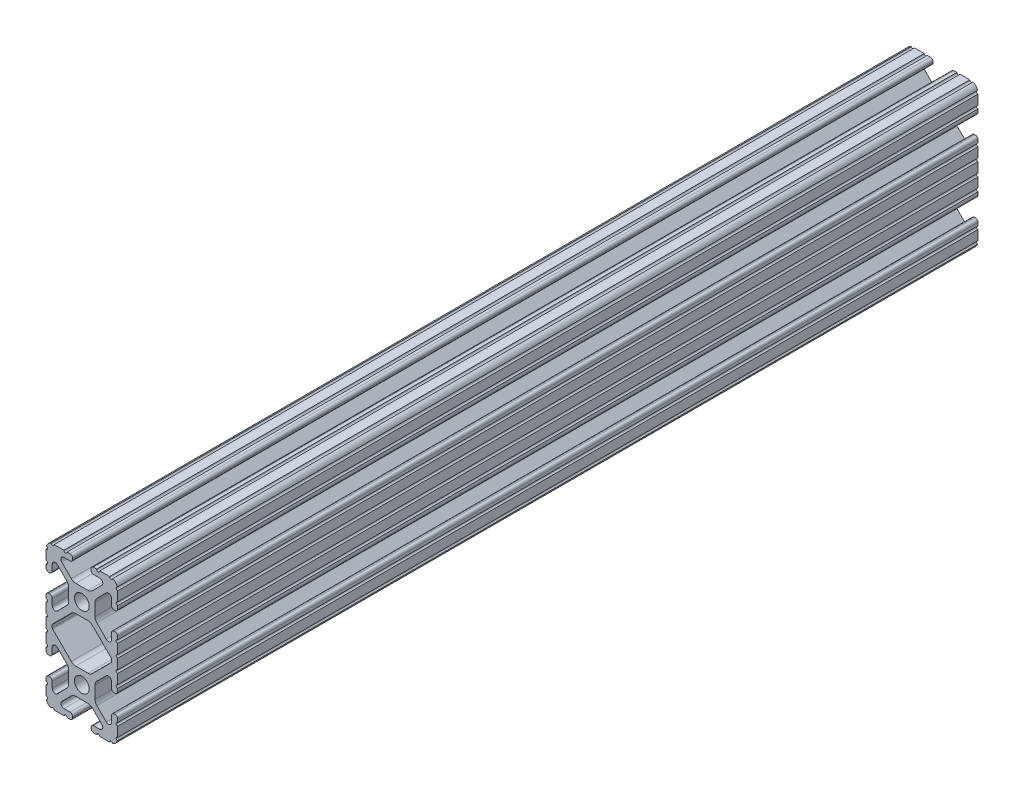
SolidWorks part; units mm, degrees
ref_plane "Front Plane" through (0, 0, 0) normal (0, 0, 1) x (1, 0, 0)
ref_plane "Top Plane" through (0, 0, 0) normal (0, 1, 0) x (1, 0, 0)
ref_plane "Right Plane" through (0, 0, 0) normal (1, 0, 0) x (0, 0, -1)
sketch "Sketch2" plane through (0, 0, 0) normal (0, 0, 1) x (1, 0, 0)
  line L0 (0, 25.4) -> (0, -25.4) construction
  line L1 (-12.7, 0) -> (12.7, 0) construction
  line L2 (3.2512, -25.4) -> (12.7, -25.4)
  line L3 (12.7, -25.4) -> (12.7, -15.9512)
  line L4 (3.2512, -25.4) -> (3.2512, -23.1902)
  line L5 (3.2512, -23.1902) -> (8.9276, -23.1902)
  line L6 (8.9276, -23.1902) -> (3.0856, -17.3482)
  line L7 (0, -12.7) -> (12.7, -25.4) construction
  line L8 (12.7, -15.9512) -> (10.4902, -15.9512)
  line L9 (10.4902, -15.9512) -> (10.4902, -21.6276)
  line L10 (10.4902, -21.6276) -> (4.6482, -15.7856)
  circle A0 centre (0, -12.7) radius 2.6035
  arc A1 (6.3485, -23.1902) -> (7.1039, -21.3665) centre (6.3485, -22.1219) ccw construction
  point P8 (0, -17.3482)
  dimension "Center Hole Diameter" = 5.207
  dimension "Rail Height" = 50.8
  dimension "Rail Width" = 25.4
  dimension "T-Slot Width" = 6.5024
  dimension "Slot Inner Width" = 14.8336
  dimension "Thickness" = 2.2098
  dimension "Slot Depth" = 5.842
  dimension "D1" = 2.2098
  dimension "C to C" = 25.4
sketch "Sketch3" plane through (0, 0, 0) normal (1, 0, 0) x (0, 0, -1)
  line L0 (-152.4, -25.4) -> (152.4, -25.4) construction
  line L1 (-127, 0) -> (127, 0) construction
  dimension "Length" = 304.8
  dimension "D1" = 25.4
sketch "Sketch4" plane through (0, 0, 0) normal (0, 0, 1) x (1, 0, 0)
  line L0 (4.1904, -25.4) -> (10.1173, -25.4)
  line L1 (3.2512, -25.4) -> (12.7, -25.4) construction
  line L2 (3.2512, -25.4) -> (3.2512, -23.1902) construction
  line L3 (3.2512, -23.1902) -> (8.9276, -23.1902) construction
  line L4 (3.2512, -24.1294) -> (3.2512, -24.4608)
  line L5 (4.1904, -23.1902) -> (6.3485, -23.1902)
  line L6 (0, -17.3482) -> (2.164, -17.3482)
  line L7 (8.9276, -23.1902) -> (3.0856, -17.3482) construction
  line L8 (3.7373, -17.9999) -> (7.1039, -21.3665)
  line L9 (12.7, -25.4) -> (12.7, -15.9512) construction
  line L10 (10.4902, -21.6276) -> (4.6482, -15.7856) construction
  line L11 (10.4902, -15.9512) -> (10.4902, -21.6276) construction
  line L12 (10.4902, -19.0485) -> (10.4902, -16.8904)
  line L13 (12.7, -15.9512) -> (10.4902, -15.9512) construction
  line L14 (11.4294, -15.9512) -> (11.7608, -15.9512)
  line L15 (12.7, -16.8904) -> (12.7, -22.8173)
  line L16 (8.6665, -19.8039) -> (5.2999, -16.4373)
  line L17 (4.6482, -12.7) -> (4.6482, -14.864)
  line L19 (0, -17.3482) -> (0, -15.3035)
  line L20 (0, 25.4) -> (0, -25.4) construction
  line L21 (4.6482, -12.7) -> (2.6035, -12.7)
  arc A0 (3.2512, -24.4608) -> (4.1904, -25.4) centre (4.1904, -24.4608) ccw
  circle A1 centre (0, -12.7) radius 2.6035 construction
  arc A2 (3.2512, -24.1294) -> (4.1904, -23.1902) centre (4.1904, -24.1294) cw
  arc A3 (6.3485, -23.1902) -> (7.1039, -21.3665) centre (6.3485, -22.1219) ccw
  arc A4 (2.164, -17.3482) -> (3.7373, -17.9999) centre (2.164, -19.5732) cw
  arc A5 (10.1173, -25.4) -> (12.7, -22.8173) centre (10.1173, -22.8173) ccw
  arc A6 (8.6665, -19.8039) -> (10.4902, -19.0485) centre (9.4219, -19.0485) ccw
  arc A7 (10.4902, -16.8904) -> (11.4294, -15.9512) centre (11.4294, -16.8904) cw
  arc A8 (11.7608, -15.9512) -> (12.7, -16.8904) centre (11.7608, -16.8904) cw
  arc A9 (5.2999, -16.4373) -> (4.6482, -14.864) centre (6.8732, -14.864) cw
  arc A11 (0, -15.3035) -> (2.6035, -12.7) centre (0, -12.7) ccw
  dimension "D1" = 2.5827
  dimension "D2" = 2.225
  dimension "D3" = 0.9392
extrude "Boss-Extrude1" add sketch "Sketch4" along normal mid plane 304.8
sketch "Sketch5" plane through (0, 0, 0) normal (0, 0, 1) x (1, 0, 0)
  line L0 (3.2512, -25.4) -> (12.7, -25.4) construction
  line L1 (4.1904, -23.1902) -> (6.3485, -23.1902) construction
  line L3 (0, -12.7) -> (12.7, -25.4) construction
  line L4 (6.3485, -23.1902) -> (6.3485, -25.4) construction
  line L5 (8.9276, -23.1902) -> (3.0856, -17.3482) construction
  circle A0 centre (10.3562, -25.4) radius 0.5524
  circle A1 centre (5.796, -25.4) radius 0.5524
  circle A2 centre (12.7, -23.0562) radius 0.5524
  circle A3 centre (12.7, -18.496) radius 0.5524
  point P10 (5.2694, -23.1902)
  point P12 (9.4219, -19.0485)
  dimension "D1" = 1.1049
extrude "Cut-Extrude1" cut sketch "Sketch5" against normal through all both and the other way through all
mirror "Mirror1" about plane through (4.6482, -12.7, 152.4) normal (0, -1, 0) of bodies 137 134
sketch "Sketch6" plane through (0, 0, 0) normal (0, 0, 1) x (1, 0, 0)
  line L0 (12.7, -1.7914) -> (12.7, 0)
  line L1 (12.7, 0) -> (9.8037, 0)
  line L2 (-12.7, 0) -> (12.7, 0) construction
  line L3 (9.8037, 0) -> (9.8037, -2.3438)
  line L4 (9.8037, -2.3438) -> (12.1476, -2.3438)
  circle A0 centre (12.7, -2.3438) radius 0.5524 construction
  arc A1 (12.7, -1.7914) -> (12.1476, -2.3438) centre (12.7, -2.3438) ccw
  arc A4 (12.58, -1.8046) -> (12.7, -2.8963) centre (12.7, -2.3438) ccw construction
  arc A6 (9.8037, 0) -> (10.8954, -0.12) centre (10.3562, 0) ccw construction
extrude "Boss-Extrude2" add sketch "Sketch6" along normal mid plane 304.8
sketch "Sketch7" plane through (0, 0, 0) normal (0, 0, 1) x (1, 0, 0)
  line L0 (5.4206, -5.7168) -> (10.3284, -0.809)
  line L1 (3.7373, -7.4001) -> (7.1039, -4.0335) construction
  line L2 (10.4902, -0.4184) -> (10.4902, 0)
  line L3 (0, 0) -> (10.4902, 0)
  line L4 (-12.7, 0) -> (12.7, 0) construction
  line L5 (0, 0) -> (5.4206, -5.7168)
  arc A0 (10.3284, -0.809) -> (10.4902, -0.4184) centre (9.9377, -0.4184) ccw
  arc A3 (12.7, -1.7914) -> (12.7, -2.8963) centre (12.7, -2.3438) ccw construction
extrude "Cut-Extrude2" cut sketch "Sketch7" against normal through all both and the other way through all
mirror "Mirror2" about plane through (0, 0, 0) normal (0, 1, 0) of bodies 139 135
mirror "Mirror3" about plane through (0, 0, 0) normal (1, 0, 0) of bodies 136
equation "\"D1@Boss-Extrude1\"=\"Length@Sketch3\""
equation "\"D1@Sketch2\"=\"Thickness@Sketch2\""
equation "\"D2@Sketch4\"=\"Slot Inner Width@Sketch2\"*0.15"
equation "\"D1@Sketch4\"=\"D3@Sketch4\"*2.75"
equation "\"D3@Sketch4\"=\"Thickness@Sketch2\"*0.425"
equation "\"D1@Sketch5\"=\"Thickness@Sketch2\"*0.5"
equation "\"D1@Boss-Extrude2\"=\"Length@Sketch3\""
